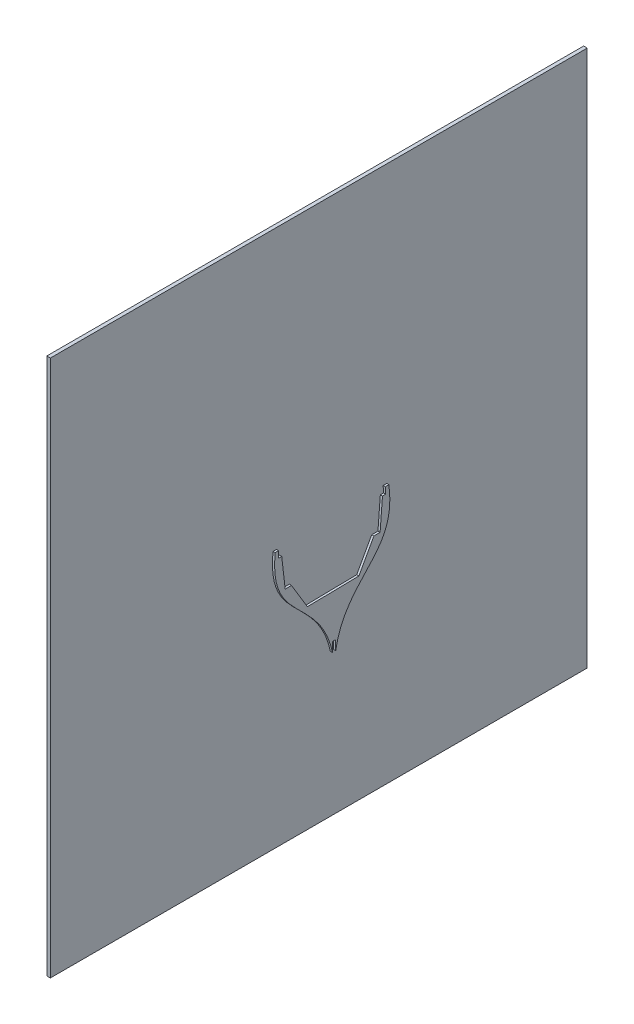
SolidWorks part; units mm, degrees
ref_plane "Plan de face" through (0, 0, 0) normal (0, 0, 1) x (1, 0, 0)
ref_plane "Plan de dessus" through (0, 0, 0) normal (0, 1, 0) x (1, 0, 0)
ref_plane "Plan de droite" through (0, 0, 0) normal (1, 0, 0) x (0, 0, -1)
sketch "Esquisse1" plane through (0, 0, 0) normal (0, 0, 1) x (1, 0, 0)
  point P0 (-20, 0)
  dimension "D1" = 20
sketch3d "Esquisse3D1"
  line L1 (-20, 1121.2893, 777.275) -> (-20, 1121.2893, -722.725)
  line L2 (-20, 1121.2893, 777.275) -> (-20, -378.7107, 777.275)
  line L3 (-20, -378.7107, 777.275) -> (-20, -378.7107, -722.725)
  line L4 (-20, 1121.2893, -722.725) -> (-20, -378.7107, -722.725)
  dimension "D1" = 1500
  dimension "D2" = 1500
extrude "Boss.-Extru.2" add sketch "Esquisse3D1" along direction (1, 0, 0) on the side of the normal blind 10 contours L2 L1 L4 L3
sketch "Esquisse4" plane through (-10, 0, 0) normal (1, 0, 0) x (0, 0, -1)
  line L0 (0, 0) -> (-7.701, 425.1082) construction
  line L1 (169.3944, 339.9131) -> (-188.5193, 333.4294) construction
  line L2 (-187.2006, 249.23) -> (169.0622, 255.6839) construction
  line L3 (-144.268, 175.2448) -> (126.4811, 180.1495) construction
sketch "Esquisse5" plane through (0, 0, 0) normal (1, 0, 0) x (0, 0, -1)
  line L0 (-7.701, 425.1082) -> (0, 0) construction
  line L2 (0, 0) -> (3.955, 18.2202) construction
  line L3 (3.955, 18.2202) -> (1.1283, 210.6022) construction
  line L4 (1.1283, 210.6022) -> (180.7047, 151.0866) construction
  line L5 (180.7047, 151.0866) -> (152.4895, 358.0487) construction
  line L8 (152.4895, 358.0487) -> (142.4895, 357.8676)
  line L9 (142.4895, 357.8676) -> (143.6253, 339.4463)
  line L10 (169.3944, 339.9131) -> (-188.5193, 333.4294) construction
  line L11 (143.6253, 339.4463) -> (134.6025, 339.2829)
  line L12 (134.6025, 339.2829) -> (128.0103, 254.9402)
  line L13 (-187.2006, 249.23) -> (169.0622, 255.6839) construction
  line L14 (128.0103, 254.9402) -> (110.594, 254.6247)
  line L15 (110.594, 254.6247) -> (68.7005, 179.1028)
  line L16 (-144.268, 175.2448) -> (126.4811, 180.1495) construction
  line L17 (68.7005, 179.1028) -> (-75.1423, 176.497)
  line L18 (0, 0) -> (-4.6123, 18.065) construction
  line L19 (-4.6123, 18.065) -> (-8.7553, 210.4232) construction
  line L20 (-8.7553, 210.4232) -> (-186.0583, 144.4425) construction
  line L21 (-186.0583, 144.4425) -> (-165.3576, 352.2908) construction
  line L22 (-119.7437, 250.452) -> (-75.1423, 176.497)
  line L23 (-137.1599, 250.1365) -> (-119.7437, 250.452)
  line L24 (-146.8026, 334.1851) -> (-137.1599, 250.1365)
  line L25 (-155.8255, 334.0216) -> (-146.8026, 334.1851)
  line L26 (-155.3576, 352.472) -> (-155.8255, 334.0216)
  line L27 (-165.3576, 352.2908) -> (-155.3576, 352.472)
  spline S0 degree 4 poles (0, 0) (3.955, 18.2202) (1.1283, 210.6022) (180.7047, 151.0866) (152.4895, 358.0487) knots 0 0 0 0 0 1 1 1 1 1
  spline S1 degree 4 poles (0, 0) (-4.6123, 18.065) (-8.7553, 210.4232) (-186.0583, 144.4425) (-165.3576, 352.2908) knots 0 0 0 0 0 1 1 1 1 1
  point P30 (-3.2209, 177.7999)
  dimension "D1" = 10
extrude "Boss.-Extru.3" add sketch "Esquisse5" along normal blind 6 separate body
sketch "Esquisse6" plane through (6, 0, 0) normal (1, 0, 0) x (0, 0, -1)
  line L0 (-5.0518, 30.3795) -> (-5.5409, 57.3795)
  line L1 (-5.5409, 57.3795) -> (3.4591, 57.5426)
  line L2 (3.4591, 57.5426) -> (3.9482, 30.5426)
  line L3 (3.9482, 30.5426) -> (117.0633, -47.527)
  line L4 (117.0633, -47.527) -> (-85.2277, -65.22)
  line L5 (-85.2277, -65.22) -> (-5.0518, 30.3795)
  line L6 (-5.0518, 30.3795) -> (3.9482, 30.5426) construction
  line L7 (-144.268, 175.2448) -> (126.4811, 180.1495) construction
  spline S0 degree 4 poles (-165.3576, 352.2908) (-186.0583, 144.4425) (-8.7553, 210.4232) (-4.6123, 18.065) (0, 0) knots 0 0 0 0 0 1 1 1 1 1 construction
  spline S1 degree 4 poles (0, 0) (3.955, 18.2202) (1.1283, 210.6022) (180.7047, 151.0866) (152.4895, 358.0487) knots 0 0 0 0 0 1 1 1 1 1 construction
  dimension "D1" = 9
  dimension "D2" = 27
extrude "Enlèv. mat.-Extru.1" cut sketch "Esquisse6" against normal blind 6
